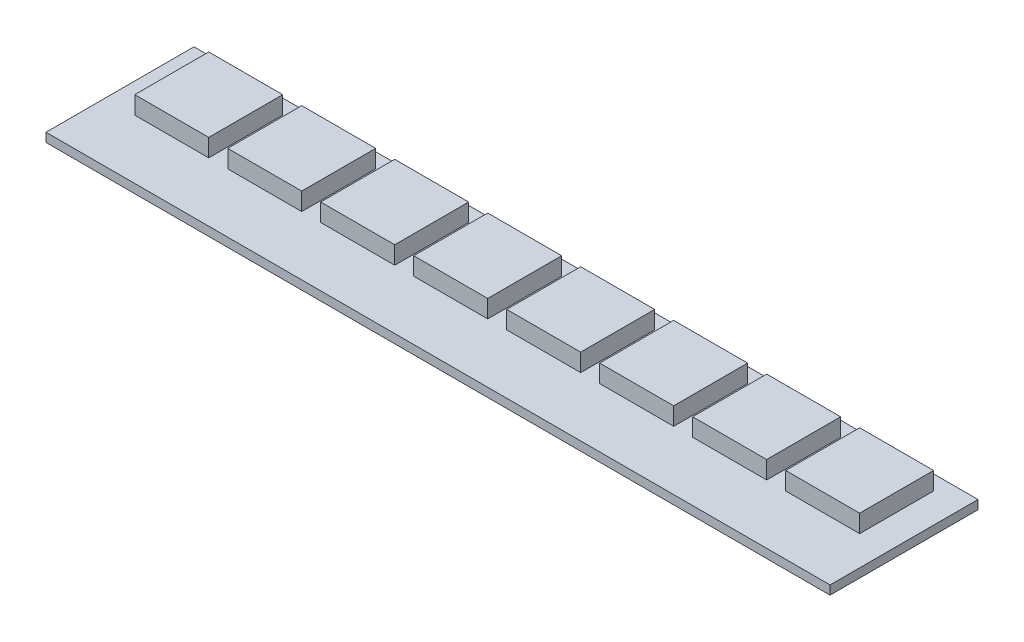
SolidWorks part; units mm, degrees
ref_plane "Front Plane" through (0, 0, 0) normal (0, 0, 1) x (1, 0, 0)
ref_plane "Top Plane" through (0, 0, 0) normal (0, 1, 0) x (1, 0, 0)
ref_plane "Right Plane" through (0, 0, 0) normal (1, 0, 0) x (0, 0, -1)
sketch "Sketch1" plane through (0, 0, 0) normal (1, 0, 0) x (0, 0, -1)
  line L1 (5, -0.3) -> (-5, -0.3)
  line L2 (5, -0.3) -> (5, 0.3)
  line L3 (5, 0.3) -> (-5, 0.3)
  line L4 (-5, -0.3) -> (-5, 0.3)
  line L5 (5, -0.3) -> (-5, 0.3) construction
  line L6 (5, 0.3) -> (-5, -0.3) construction
  point P0 (0, 0)
  dimension "D1" = 0.6
  dimension "D2" = 10
extrude "Boss-Extrude1" add sketch "Sketch1" along normal mid plane 53
sketch "Sketch2" plane through (0, 0.3, 0) normal (0, 1, 0) x (1, 0, 0)
  line L0 (0, 0) -> (0, 5) construction
  line L1 (26.5, 5) -> (-26.5, 5) construction
  line L2 (-13.2143, -1) -> (-18.2143, -1)
  line L3 (-19.5, -1) -> (-24.5, -1)
  line L4 (-19.5, -1) -> (-19.5, 4)
  line L5 (-19.5, 4) -> (-24.5, 4)
  line L6 (-24.5, -1) -> (-24.5, 4)
  line L7 (-19.5, -1) -> (-24.5, 4) construction
  line L8 (-19.5, 4) -> (-24.5, -1) construction
  line L9 (-13.2143, -1) -> (-13.2143, 4)
  line L10 (-13.2143, 4) -> (-18.2143, 4)
  line L11 (-18.2143, -1) -> (-18.2143, 4)
  line L12 (-13.2143, -1) -> (-18.2143, 4) construction
  line L13 (-13.2143, 4) -> (-18.2143, -1) construction
  line L14 (-6.9286, -1) -> (-11.9286, -1)
  line L15 (-6.9286, -1) -> (-6.9286, 4)
  line L16 (-6.9286, 4) -> (-11.9286, 4)
  line L17 (-11.9286, -1) -> (-11.9286, 4)
  line L18 (-6.9286, -1) -> (-11.9286, 4) construction
  line L19 (-6.9286, 4) -> (-11.9286, -1) construction
  line L20 (-0.6429, -1) -> (-5.6429, -1)
  line L21 (-0.6429, -1) -> (-0.6429, 4)
  line L22 (-0.6429, 4) -> (-5.6429, 4)
  line L23 (-5.6429, -1) -> (-5.6429, 4)
  line L24 (-0.6429, -1) -> (-5.6429, 4) construction
  line L25 (-0.6429, 4) -> (-5.6429, -1) construction
  line L26 (5.6429, -1) -> (0.6429, -1)
  line L27 (5.6429, -1) -> (5.6429, 4)
  line L28 (5.6429, 4) -> (0.6429, 4)
  line L29 (0.6429, -1) -> (0.6429, 4)
  line L30 (5.6429, -1) -> (0.6429, 4) construction
  line L31 (5.6429, 4) -> (0.6429, -1) construction
  line L32 (11.9286, -1) -> (6.9286, -1)
  line L33 (11.9286, -1) -> (11.9286, 4)
  line L34 (11.9286, 4) -> (6.9286, 4)
  line L35 (6.9286, -1) -> (6.9286, 4)
  line L36 (11.9286, -1) -> (6.9286, 4) construction
  line L37 (11.9286, 4) -> (6.9286, -1) construction
  line L38 (18.2143, -1) -> (13.2143, -1)
  line L39 (18.2143, -1) -> (18.2143, 4)
  line L40 (18.2143, 4) -> (13.2143, 4)
  line L41 (13.2143, -1) -> (13.2143, 4)
  line L42 (18.2143, -1) -> (13.2143, 4) construction
  line L43 (18.2143, 4) -> (13.2143, -1) construction
  line L44 (24.5, -1) -> (19.5, -1)
  line L45 (24.5, -1) -> (24.5, 4)
  line L46 (24.5, 4) -> (19.5, 4)
  line L47 (19.5, -1) -> (19.5, 4)
  line L48 (24.5, -1) -> (19.5, 4) construction
  line L49 (24.5, 4) -> (19.5, -1) construction
  line L50 (-3.1429, 1.5) -> (3.1429, 1.5) construction
  line L51 (-26.5, 5) -> (-26.5, -5) construction
  point P4 (-22, 1.5)
  point P12 (-15.7143, 1.5)
  point P17 (-9.4286, 1.5)
  point P22 (-3.1429, 1.5)
  point P27 (3.1429, 1.5)
  point P32 (9.4286, 1.5)
  point P37 (15.7143, 1.5)
  point P42 (22, 1.5)
  dimension "D1" = 5
  dimension "D2" = 1
  dimension "D3" = 5
  dimension "D5" = 2
  dimension "D4" = 8
extrude "Boss-Extrude2" add sketch "Sketch2" along normal blind 1.2
